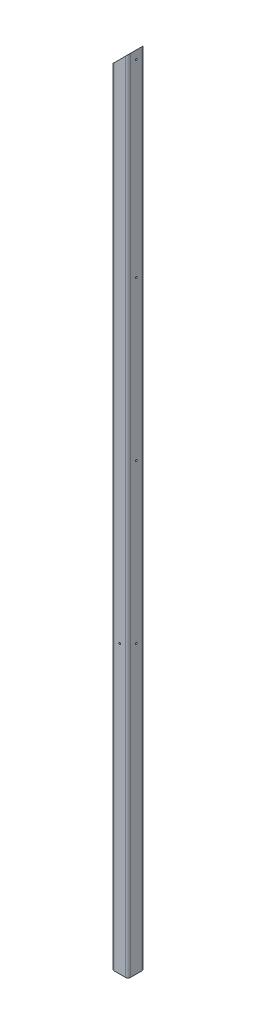
SolidWorks part; units mm, degrees
ref_plane "Front Plane" through (0, 0, 0) normal (0, 0, 1) x (1, 0, 0)
ref_plane "Top Plane" through (0, 0, 0) normal (0, 1, 0) x (1, 0, 0)
ref_plane "Right Plane" through (0, 0, 0) normal (1, 0, 0) x (0, 0, -1)
sketch "Sketch1" plane through (0, 0, 0) normal (0, 0, 1) x (1, 0, 0)
  line L0 (0, 0) -> (0, 1920)
  dimension "D1" = 1920
other "Tube (square) 40 X 40 X 3.2(1)"
ref_plane "Plane1" through (0, 0, 0) normal (0, 1, 0) x (-1, 0, 0)
sketch "Sketch15" plane through (0, 0, 0) normal (0, 1, 0) x (-1, 0, 0)
  line L0 (-13.6, -16.8) -> (13.6, -16.8)
  line L1 (-16.8, -13.6) -> (-16.8, 13.6)
  line L2 (13.6, 16.8) -> (-13.6, 16.8)
  line L3 (16.8, 13.6) -> (16.8, -13.6)
  line L4 (-13.6, -20) -> (13.6, -20)
  line L5 (-20, -13.6) -> (-20, 13.6)
  line L6 (13.6, 20) -> (-13.6, 20)
  line L7 (20, 13.6) -> (20, -13.6)
  line L8 (-20, 0) -> (-16.8, 0) construction
  line L9 (-16.8, 0) -> (16.8, 0) construction
  line L10 (16.8, 0) -> (20, 0) construction
  line L12 (0, 20) -> (0, 16.8) construction
  line L13 (0, 16.8) -> (0, -16.8) construction
  line L14 (0, -16.8) -> (0, -20) construction
  arc A0 (20, 13.6) -> (13.6, 20) centre (13.6, 13.6) ccw
  arc A1 (13.6, -20) -> (20, -13.6) centre (13.6, -13.6) ccw
  arc A2 (-20, -13.6) -> (-13.6, -20) centre (-13.6, -13.6) ccw
  arc A3 (-13.6, 20) -> (-20, 13.6) centre (-13.6, 13.6) ccw
  arc A4 (-13.6, 16.8) -> (-16.8, 13.6) centre (-13.6, 13.6) ccw
  arc A5 (16.8, 13.6) -> (13.6, 16.8) centre (13.6, 13.6) ccw
  arc A6 (13.6, -16.8) -> (16.8, -13.6) centre (13.6, -13.6) ccw
  arc A7 (-16.8, -13.6) -> (-13.6, -16.8) centre (-13.6, -13.6) ccw
  point P2 (-20, 20)
  point P33 (-20, -20)
  point P34 (20, -20)
  point P36 (20, 20)
  point P37 (0, 0)
  dimension "D1" = 6.4
  dimension "Thickness" = 3.2
  dimension "V_leg" = 40
  dimension "H_leg" = 40
ref_plane "Plane2" through (0, 0, -20) normal (0, 0, -1) x (-1, 0, 0)
sketch "Sketch13" plane through (0, 0, -20) normal (0, 0, -1) x (-1, 0, 0)
  line L2 (20, 1920) -> (20, 0) construction
  line L3 (20, 1920) -> (20, 1880)
  line L4 (-13.6, 1920) -> (13.6, 1920) construction
  line L5 (-20, 1920) -> (20, 1920)
  line L9 (20, 1880) -> (-20, 1920)
  line L10 (20, 1920) -> (20, 1880)
  dimension "D1" = 40
extrude "Cut-Extrude1" cut sketch "Sketch13" against normal through all contours L9 L3 L5
ref_plane "Plane3" through (20, 0, 0) normal (1, 0, 0) x (0, 0, -1)
sketch "Sketch16" plane through (20, 0, 0) normal (1, 0, 0) x (0, 0, -1)
  line L0 (-13.6, 1920) -> (13.6, 1920) construction
  line L1 (-13.6, 1920) -> (13.6, 1920) construction
  line L2 (-13.6, 1900) -> (13.6, 1900) construction
  line L3 (-13.6, 1447) -> (13.6, 1447) construction
  line L4 (-13.6, 1067) -> (13.6, 1067) construction
  line L5 (-13.6, 687) -> (13.6, 687) construction
  circle A0 centre (0, 1900) radius 2
  circle A1 centre (0, 1447) radius 2
  circle A2 centre (0, 1067) radius 2
  circle A3 centre (0, 687) radius 2
  dimension "D4" = 4
  dimension "D5" = 1233
  dimension "D1" = 20
  dimension "D2" = 453
  dimension "D3" = 833
extrude "Cut-Extrude2" cut sketch "Sketch16" against normal blind 3
ref_plane "Plane4" through (0, 0, 20) normal (0, 0, 1) x (1, 0, 0)
sketch "Sketch17" plane through (0, 0, 20) normal (0, 0, 1) x (1, 0, 0)
  line L0 (-13.6, 687) -> (13.6, 687) construction
  line L1 (-13.6, 0) -> (13.6, 0) construction
  line L2 (-13.6, 0) -> (13.6, 0) construction
  circle A0 centre (0, 687) radius 2
  dimension "D2" = 4
  dimension "D1" = 687
extrude "Cut-Extrude3" cut sketch "Sketch17" against normal blind 3
